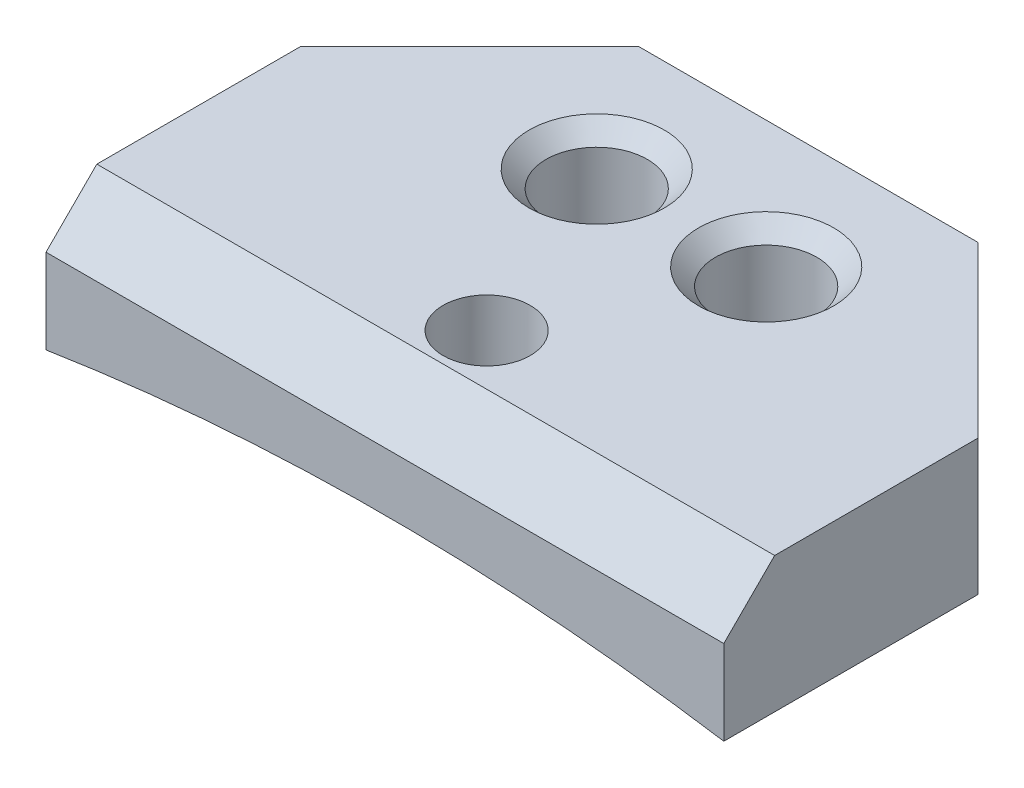
SolidWorks part; units mm, degrees
ref_plane "Front Plane" through (0, 0, 0) normal (0, 0, 1) x (1, 0, 0)
ref_plane "Top Plane" through (0, 0, 0) normal (0, 1, 0) x (1, 0, 0)
ref_plane "Right Plane" through (0, 0, 0) normal (1, 0, 0) x (0, 0, -1)
sketch "Sketch1" plane through (0, 0, 0) normal (0, 1, 0) x (1, 0, 0)
  line L0 (-28.5118, -10.9672) -> (-22.1618, -4.6172)
  line L1 (-22.1618, -4.6172) -> (-9.4618, -4.6172)
  line L2 (-28.5118, -10.9672) -> (-28.5118, -12.5547)
  line L3 (-28.5118, -12.5547) -> (-3.1118, -12.5547)
  line L4 (-3.1118, -10.9672) -> (-3.1118, -12.5547)
  line L5 (-9.4618, -4.6172) -> (-3.1118, -10.9672)
  line L6 (-15.8118, -12.5547) -> (-15.8118, -4.6172) construction
  line L8 (-3.1118, -10.9672) -> (-3.1118, -4.6172) construction
  line L9 (-3.1118, -4.6172) -> (-9.4618, -4.6172) construction
  dimension "D1" = 12.7
  dimension "D2" = 7.9375
  dimension "D3" = 25.4
extrude "Boss-Extrude1" add sketch "Sketch1" along normal blind 3.175
sketch "Sketch2" plane through (0, 0, 12.5547) normal (0, 0, 1) x (1, 0, 0)
  circle A0 centre (-15.8118, -82.8523) radius 83.82
  dimension "D1" = 167.64
extrude "Cut-Extrude1" cut sketch "Sketch2" against normal through all both and the other way through all
sketch "Sketch5" plane through (0, 0, 4.6172) normal (0, 0, -1) x (-1, 0, 0)
  line L0 (3.1118, 3.175) -> (3.1118, 0) construction
  line L1 (3.1118, 3.175) -> (3.1118, 0)
  line L4 (28.5118, 3.175) -> (28.5118, 0) construction
  line L5 (28.5118, 3.175) -> (28.5118, 0)
  line L6 (28.5118, -1.9021) -> (28.5118, 0)
  line L7 (3.1118, -1.9021) -> (3.1118, 0)
  line L8 (3.1118, 3.175) -> (28.5118, 3.175)
  arc A0 (3.1118, -1.9021) -> (28.5118, -1.9021) centre (15.8118, -82.8523) cw
  arc A1 (28.5118, 0) -> (3.1118, 0) centre (15.8118, -82.8523) ccw construction
  arc A2 (28.5118, 0) -> (3.1118, 0) centre (15.8118, -82.8523) ccw construction
  dimension "D1" = 81.9404
extrude "Boss-Extrude2" add sketch "Sketch5" against normal blind 15.875
chamfer "Chamfer1" distance 6.35 angle 45 2 edges at (-28.5118, 0.6365, 4.6172) (-3.1118, 0.6365, 4.6172)
hole_wizard "#10-24 Tapped Hole1" positions "Sketch3" profile "Sketch4" tap size "#10-24" standard "ANSI Inch" end condition through all
sketch "Sketch3" plane through (0, 3.175, 0) normal (0, 1, 0) x (1, 0, 0)
  line L0 (-15.8118, -4.6172) -> (-15.8118, 3.4006) construction
  line L1 (-9.4618, -4.6172) -> (-22.1618, -4.6172) construction
  point P0 (-18.9868, -9.3797)
  point P12 (-12.6368, -9.3797)
  dimension "D1" = 4.7625
  dimension "D2" = 3.175
sketch "Sketch4" plane through (-18.9868, 3.175, 9.3797) normal (1, 0, 0) x (0, 0, 1)
  line L0 (0, 0) -> (0, 5.0771)
  line L1 (0, 5.0771) -> (1.8986, 5.0771)
  line L2 (1.8986, 5.0771) -> (1.8986, 0.635)
  line L3 (1.8986, 0.635) -> (2.5337, 0)
  line L5 (2.5337, 0) -> (0, 0)
  line L6 (-1.8986, 0.635) -> (-2.5337, 0) construction
  line L11 (0, -6.35) -> (0, 107.95) construction
  dimension "Thru Tap Drill Dia." = 3.7973
  dimension "Thru Tap Drill Depth" = 5.0771
  dimension "Near C'Sink Dia." = 5.0673
  dimension "Near C'Sink Angle" = 90
cosmetic thread "Hole Thread3" parameters "D2"=4.826
cosmetic thread "Hole Thread4" parameters "D2"=4.826
chamfer "Chamfer2" distance 1.905 angle 45 1 edges at (-15.8118, 3.175, 20.4922)
sketch "Sketch6" plane through (0, 3.175, 0) normal (0, 1, 0) x (1, 0, 0)
  circle A0 centre (-15.81, -16.6822) radius 1.6319 construction
  circle A1 centre (-15.81, -16.6822) radius 1.6319
extrude "Cut-Extrude2" cut sketch "Sketch6" against normal through all
